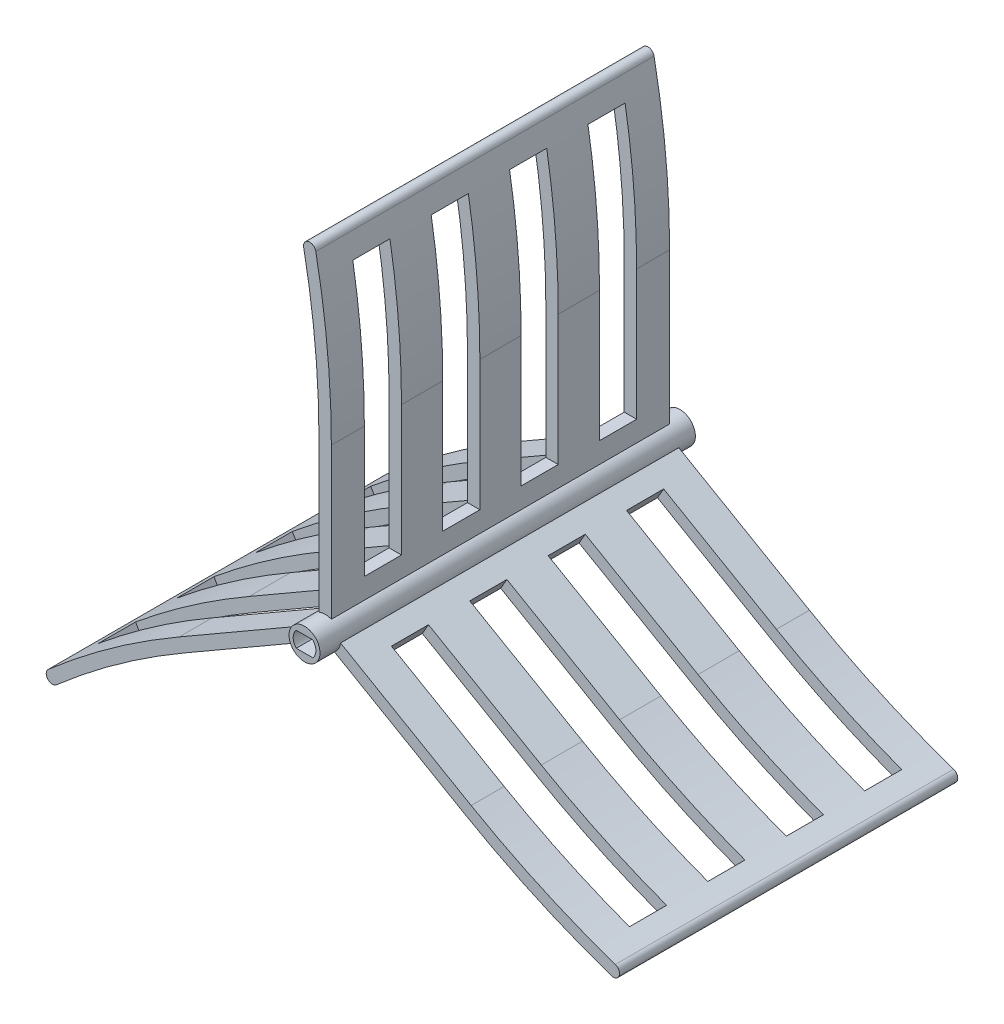
SolidWorks part; units mm, degrees
ref_plane "前视基准面" through (0, 0, 0) normal (0, 0, 1) x (1, 0, 0)
ref_plane "上视基准面" through (0, 0, 0) normal (0, 1, 0) x (1, 0, 0)
ref_plane "右视基准面" through (0, 0, 0) normal (1, 0, 0) x (0, 0, -1)
other "Configuration Table"
sketch "草图1" plane through (0, 0, 0) normal (0, 0, 1) x (1, 0, 0)
  circle A0 centre (0, 0) radius 3.75
  dimension "D1" = 7.5
extrude "凸台-拉伸1" add sketch "草图1" along normal blind 91
sketch "草图2" plane through (0, 0, 0) normal (0, 0, -1) x (-1, 0, 0)
  line L0 (-2, 1.8875) -> (2, 1.8875)
  line L1 (-2, -1.8875) -> (2, -1.8875)
  arc A0 (2, -1.8875) -> (2, 1.8875) centre (0, 0) ccw
  arc A1 (-2, 1.8875) -> (-2, -1.8875) centre (0, 0) ccw
  dimension "D1" = 5.5
  dimension "D2" = 4
extrude "切除-拉伸1" cut sketch "草图2" against normal blind 9
sketch "草图4" plane through (0, 0, 91) normal (0, 0, 1) x (1, 0, 0)
  circle A0 centre (0, 0) radius 2.5
  dimension "D1" = 5
extrude "凸台-拉伸2" add sketch "草图4" along normal blind 6
sketch "草图7" plane through (0, 0, 0) normal (0, 0, -1) x (-1, 0, 0)
  line L0 (0, 0) -> (0, 64) construction
  line L1 (0, 0) -> (0, 40)
  line L4 (3.7406, 80) -> (5.8189, 80) construction
  line L6 (1.5, 0) -> (1.5, 40)
  line L7 (-1.5, 0) -> (-1.5, 40)
  line L8 (1.5, 0) -> (1.5, 40)
  line L9 (-1.5, 0) -> (-1.5, 40)
  line L10 (1.5, 0) -> (-1.5, 0)
  arc A0 (0, 40) -> (4.0349, 79.9709) centre (200, 40) cw construction
  arc A3 (1.5, 40) -> (5.2126, 78.2112) centre (200, 40) cw
  arc A4 (-1.5, 40) -> (2.2687, 78.7887) centre (200, 40) cw
  arc A5 (5.2118, 78.2075) -> (2.2687, 78.7887) centre (3.7406, 78.5) ccw
  arc A6 (1.5, 40) -> (5.5046, 79.6711) centre (200, 40) cw construction
  arc A7 (-1.5, 40) -> (2.5651, 80.2706) centre (200, 40) cw construction
  dimension "D1" = 64
  dimension "D3" = 200
  dimension "D7" = 3
  dimension "D8" = 1.5
  dimension "D2" = 40
  dimension "D4" = 80
  dimension "D9" = 1.5
  dimension "D5" = 1.5
  dimension "D6" = 1.5
extrude "凸台-拉伸3" add sketch "草图7" against normal offset from surface (82 mm away) 5 from offset 4 offset against normal yes
sketch "草图10" plane through (0, 0, 97) normal (0, 0, 1) x (1, 0, 0)
  circle A0 centre (0, 0) radius 2.5
  dimension "D1" = 5
extrude "凸台-拉伸4" add sketch "草图10" along normal blind 2
sketch "草图11" plane through (0, 0, 9) normal (0, 0, -1) x (-1, 0, 0)
  line L2 (-2, -1.8875) -> (2, -1.8875)
  line L3 (2, 1.8875) -> (-2, 1.8875)
  line L4 (-2, -1.8875) -> (2, -1.8875)
  line L5 (2, 1.8875) -> (-2, 1.8875)
  arc A2 (-2, 1.8875) -> (-2, -1.8875) centre (0, 0) ccw
  arc A3 (2, -1.8875) -> (2, 1.8875) centre (0, 0) ccw
  arc A4 (-2, 1.8875) -> (-2, -1.8875) centre (0, 0) ccw
  arc A5 (2, -1.8875) -> (2, 1.8875) centre (0, 0) ccw
  dimension "D1" = 0
extrude "凸台-拉伸5" add sketch "草图11" along normal blind 3
sketch "草图12" plane through (0, 0, 6) normal (0, 0, -1) x (-1, 0, 0)
  line L2 (-2, -1.8875) -> (2, -1.8875)
  line L3 (2, 1.8875) -> (-2, 1.8875)
  line L4 (-2, -1.8875) -> (2, -1.8875)
  line L5 (2, 1.8875) -> (-2, 1.8875)
  arc A2 (-2, 1.8875) -> (-2, -1.8875) centre (0, 0) ccw
  arc A3 (2, -1.8875) -> (2, 1.8875) centre (0, 0) ccw
  arc A4 (-2, 1.8875) -> (-2, -1.8875) centre (0, 0) ccw
  arc A5 (2, -1.8875) -> (2, 1.8875) centre (0, 0) ccw
  dimension "D1" = 0
extrude "凸台-拉伸6" add sketch "草图12" along normal blind 1.5
sketch "草图13" plane through (0, 0, 4.5) normal (0, 0, -1) x (-1, 0, 0)
  line L2 (-2, -1.8875) -> (2, -1.8875)
  line L3 (2, 1.8875) -> (-2, 1.8875)
  line L4 (-2, -1.8875) -> (2, -1.8875)
  line L5 (2, 1.8875) -> (-2, 1.8875)
  arc A2 (-2, 1.8875) -> (-2, -1.8875) centre (0, 0) ccw
  arc A3 (2, -1.8875) -> (2, 1.8875) centre (0, 0) ccw
  arc A4 (-2, 1.8875) -> (-2, -1.8875) centre (0, 0) ccw
  arc A5 (2, -1.8875) -> (2, 1.8875) centre (0, 0) ccw
  dimension "D1" = 0
extrude "切除-拉伸4" cut sketch "草图13" against normal blind 0.5
sketch "草图14" plane through (0, 0, 99) normal (0, 0, 1) x (1, 0, 0)
  circle A0 centre (0, 0) radius 2.5
  dimension "D1" = 5
extrude "切除-拉伸5" cut sketch "草图14" against normal up to surface (8 mm away) up to face at (2.5, 0, 91)
sketch "草图15" plane through (0, 0, 91) normal (0, 0, 1) x (1, 0, 0)
  line L2 (-2, -1.8875) -> (2, -1.8875)
  line L3 (2, 1.8875) -> (-2, 1.8875)
  line L4 (-2, -1.8875) -> (2, -1.8875)
  line L5 (2, 1.8875) -> (-2, 1.8875)
  arc A2 (2, -1.8875) -> (2, 1.8875) centre (0, 0) ccw
  arc A3 (-2, 1.8875) -> (-2, -1.8875) centre (0, 0) ccw
  arc A4 (2, -1.8875) -> (2, 1.8875) centre (0, 0) ccw
  arc A5 (-2, 1.8875) -> (-2, -1.8875) centre (0, 0) ccw
  dimension "D1" = 0
extrude "切除-拉伸9" cut sketch "草图15" against normal blind 8
sketch "草图16" plane through (1.5, 0, 0) normal (1, 0, 0) x (0, 0, -1)
  line L0 (-4, 3.4369) -> (-4, 40) construction
  line L1 (-78, 8.4369) -> (-69, 8.4369)
  line L2 (-78, 8.4369) -> (-78, 73.4369)
  line L3 (-78, 73.4369) -> (-69, 73.4369)
  line L4 (-69, 8.4369) -> (-69, 73.4369)
  line L5 (-59, 8.4369) -> (-50, 8.4369)
  line L6 (-59, 8.4369) -> (-59, 73.4369)
  line L7 (-59, 73.4369) -> (-50, 73.4369)
  line L8 (-50, 8.4369) -> (-50, 73.4369)
  line L9 (-40, 8.4369) -> (-31, 8.4369)
  line L10 (-40, 8.4369) -> (-40, 73.4369)
  line L11 (-40, 73.4369) -> (-31, 73.4369)
  line L12 (-31, 8.4369) -> (-31, 73.4369)
  line L13 (-21, 8.4369) -> (-12, 8.4369)
  line L14 (-21, 8.4369) -> (-21, 73.4369)
  line L15 (-21, 73.4369) -> (-12, 73.4369)
  line L16 (-12, 8.4369) -> (-12, 73.4369)
  line L17 (-86, 3.4369) -> (-86, 40) construction
  line L18 (-86, 3.4369) -> (-4, 3.4369) construction
  dimension "D1" = 8
  dimension "D2" = 8
  dimension "D3" = 10
  dimension "D4" = 10
  dimension "D5" = 9
  dimension "D6" = 9
  dimension "D7" = 9
  dimension "D8" = 5
  dimension "D9" = 65
  dimension "D10" = 9
extrude "切除-拉伸10" cut sketch "草图16" against normal up to next
pattern_circular "阵列(圆周)1" count 3 over 360 about axis through (0, 0, 0) along (0, 0, 1) of "凸台-拉伸3"
pattern_circular "阵列(圆周)2" count 3 over 360 about axis through (0, 0, 0) along (0, 0, 1) of "切除-拉伸10"
